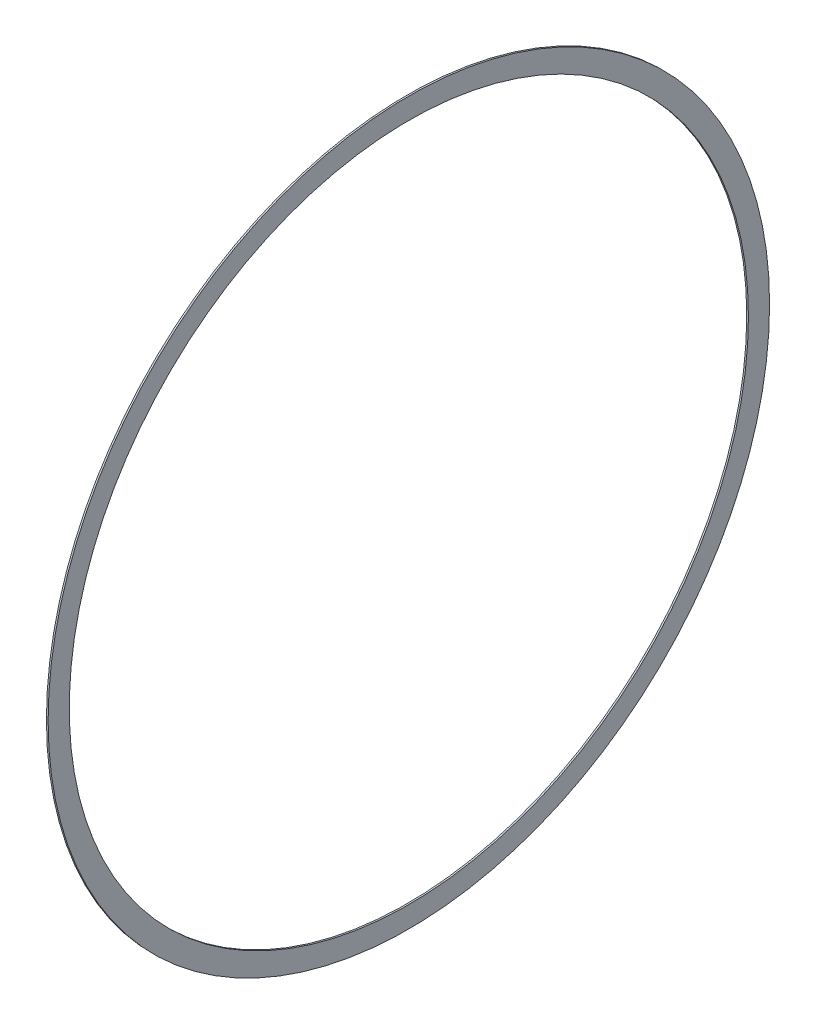
SolidWorks part; units mm, degrees
material "1023 Carbon Steel Sheet (SS)"
ref_plane "Front Plane" through (0, 0, 0) normal (0, 0, 1) x (1, 0, 0)
ref_plane "Top Plane" through (0, 0, 0) normal (0, 1, 0) x (1, 0, 0)
ref_plane "Right Plane" through (0, 0, 0) normal (1, 0, 0) x (0, 0, -1)
sketch "Sketch1" plane through (0, 0, 0) normal (1, 0, 0) x (0, 0, -1)
  circle A0 centre (0, 0) radius 803
  circle A1 centre (0, 0) radius 853
  dimension "D1" = 1606
  dimension "D2" = 50
extrude "Boss-Extrude1" add sketch "Sketch1" along normal blind 4
